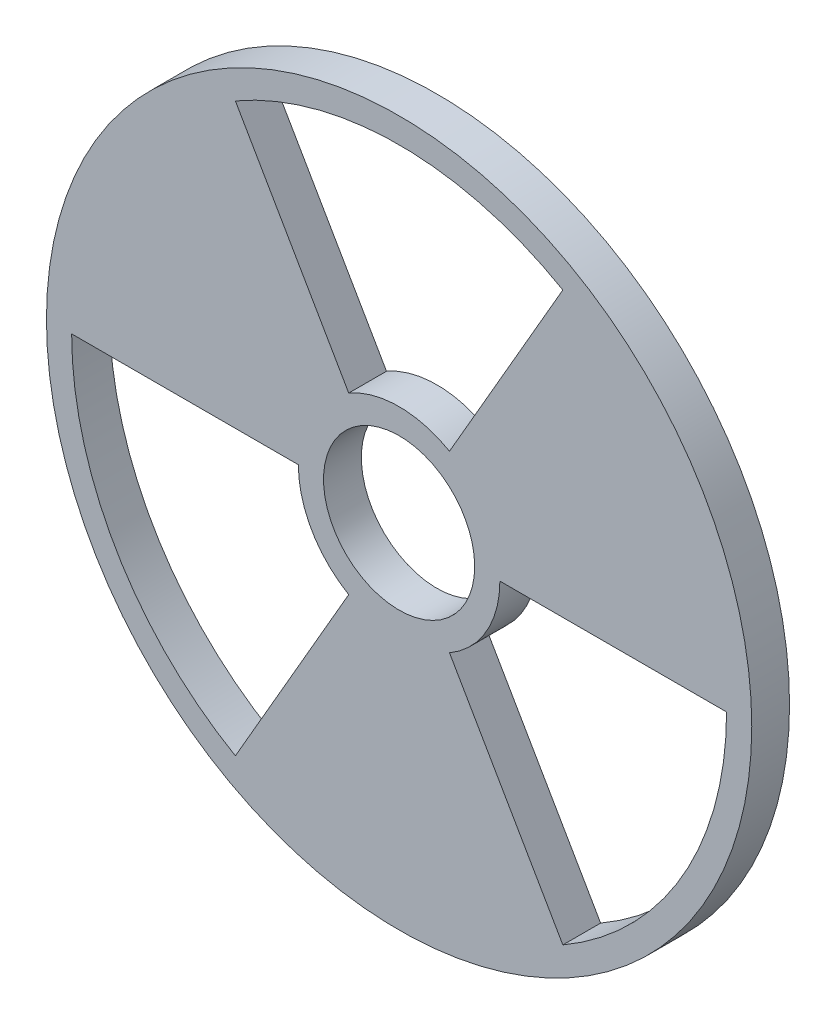
SolidWorks part; units mm, degrees
ref_plane "前视基准面" through (0, 0, 0) normal (0, 0, 1) x (1, 0, 0)
ref_plane "上视基准面" through (0, 0, 0) normal (0, 1, 0) x (1, 0, 0)
ref_plane "右视基准面" through (0, 0, 0) normal (1, 0, 0) x (0, 0, -1)
other "Configuration Table"
sketch "草图1" plane through (0, 0, 0) normal (0, 0, 1) x (1, 0, 0)
  line L0 (-13, 22.5167) -> (-4, 6.9282)
  line L1 (13, 22.5167) -> (4, 6.9282)
  line L2 (-13, -22.5167) -> (-4, -6.9282)
  line L3 (-26, 0) -> (-8, 0)
  line L6 (13, -22.5167) -> (4, -6.9282)
  line L7 (26, 0) -> (8, 0)
  circle A0 centre (0, 0) radius 30 construction
  circle A1 centre (0, 0) radius 28
  circle A2 centre (0, 0) radius 6
  arc A3 (-13, 22.5167) -> (13, 22.5167) centre (0, 0) cw
  arc A4 (-4, 6.9282) -> (4, 6.9282) centre (0, 0) cw
  arc A5 (-13, -22.5167) -> (-26, 0) centre (0, 0) cw
  arc A6 (-4, -6.9282) -> (-8, 0) centre (0, 0) cw
  arc A9 (8, 0) -> (4, -6.9282) centre (0, 0) cw
  arc A10 (26, 0) -> (13, -22.5167) centre (0, 0) cw
  point P7 (0, 0)
  point P8 (0, 26)
  point P12 (0, 8)
  point P17 (-22.5167, -13)
  point P21 (-6.9282, -4)
  point P23 (8.4293, -53.4203)
  point P25 (97.0348, -21.0859)
  point P28 (21.1572, -40.6924)
  point P29 (97.0348, -39.0859)
  dimension "D1" = 60
  dimension "D2" = 56
  dimension "D3" = 12
  dimension "D4" = 26
  dimension "D5" = 8
  dimension "D6" = 60
  dimension "D12" = 8
  dimension "D13" = 26
  dimension "D7" = 60
  dimension "D8" = 60
  dimension "D9" = 60
  dimension "D10" = 26
  dimension "D11" = 8
  dimension "D14" = 60
  dimension "D15" = 60
  dimension "D16" = 60
  dimension "D17" = 60
  dimension "D18" = 18
  dimension "D19" = 18
extrude "凸台-拉伸1" add sketch "草图1" along normal blind 3
